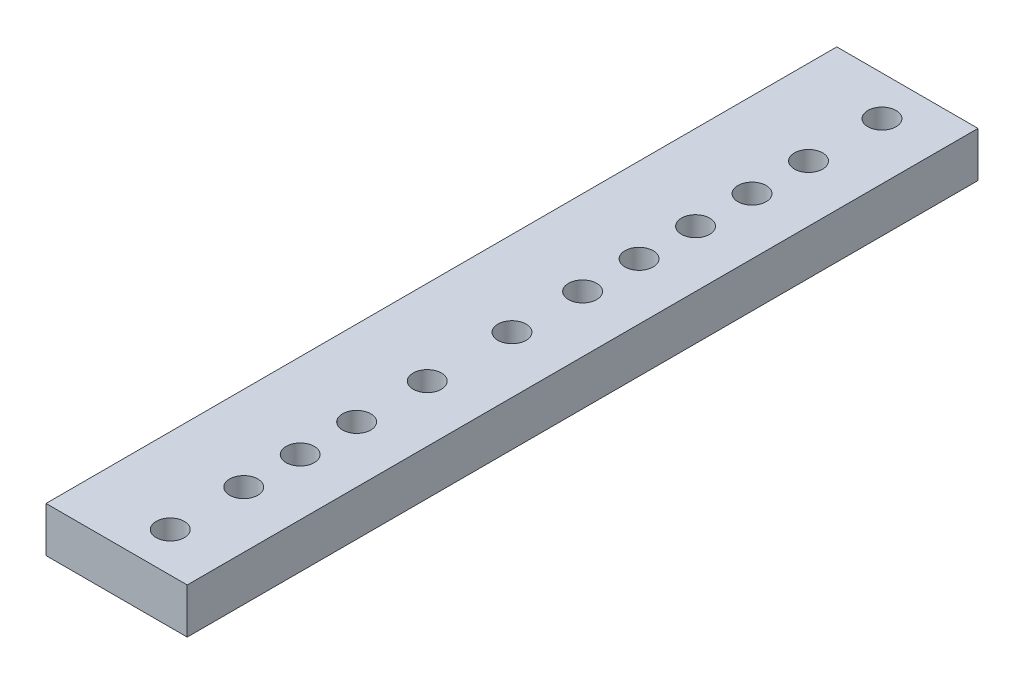
SolidWorks part; units mm, degrees
ref_plane "Front Plane" through (0, 0, 0) normal (0, 0, 1) x (1, 0, 0)
ref_plane "Top Plane" through (0, 0, 0) normal (0, 1, 0) x (1, 0, 0)
ref_plane "Right Plane" through (0, 0, 0) normal (1, 0, 0) x (0, 0, -1)
sketch "Sketch1" plane through (0, 0, 0) normal (0, 1, 0) x (1, 0, 0)
  line L1 (0, 0) -> (25, 0)
  line L2 (0, 0) -> (0, 140)
  line L3 (0, 140) -> (25, 140)
  line L4 (25, 0) -> (25, 140)
  dimension "D1" = 140
  dimension "D2" = 25
extrude "Boss-Extrude1" add sketch "Sketch1" along normal blind 8
sketch "Sketch2" plane through (0, 8, 0) normal (0, 1, 0) x (1, 0, 0)
  line L0 (0, 0) -> (25, 0) construction
  line L1 (0, 140) -> (0, 0) construction
  circle A0 centre (15, 7) radius 2.5
  circle A1 centre (15, 20) radius 2.5
  circle A2 centre (15, 30) radius 2.5
  circle A3 centre (15, 40) radius 2.5
  circle A4 centre (15, 52.5) radius 2.5
  point P14 (0, 0)
  point P16 (0, 0)
  dimension "D1" = 5
  dimension "D4" = 5
  dimension "D5" = 20
  dimension "D7" = 5
  dimension "D11" = 5
  dimension "D13" = 5
  dimension "D2" = 7
  dimension "D3" = 15
  dimension "D6" = 15
  dimension "D8" = 15
  dimension "D9" = 10
  dimension "D10" = 10
  dimension "D12" = 15
  dimension "D14" = 12.5
  dimension "D15" = 15
extrude "Cut-Extrude1" cut sketch "Sketch2" against normal through all
sketch "Sketch3" plane through (0, 0, 0) normal (0, -1, 0) x (-1, 0, 0)
  circle A0 centre (-14.9984, 67.5) radius 2.5
  circle A1 centre (-14.9979, 80) radius 2.5
  circle A2 centre (-14.9976, 90) radius 2.5
  circle A3 centre (-14.9975, 100) radius 2.5
  circle A4 centre (-14.9974, 110) radius 2.5
  circle A5 centre (-14.9973, 120) radius 2.5
  circle A6 centre (-14.9973, 133) radius 2.5
  circle A7 centre (-15, 52.5) radius 2.5 construction
  dimension "D2" = 5
  dimension "D4" = 5
  dimension "D6" = 5
  dimension "D9" = 5
  dimension "D10" = 5
  dimension "D12" = 5
  dimension "D14" = 5
  dimension "D1" = 15
  dimension "D3" = 12.5
  dimension "D5" = 10
  dimension "D7" = 10
  dimension "D8" = 10
  dimension "D11" = 10
  dimension "D13" = 13
extrude "Cut-Extrude2" cut sketch "Sketch3" against normal through all
